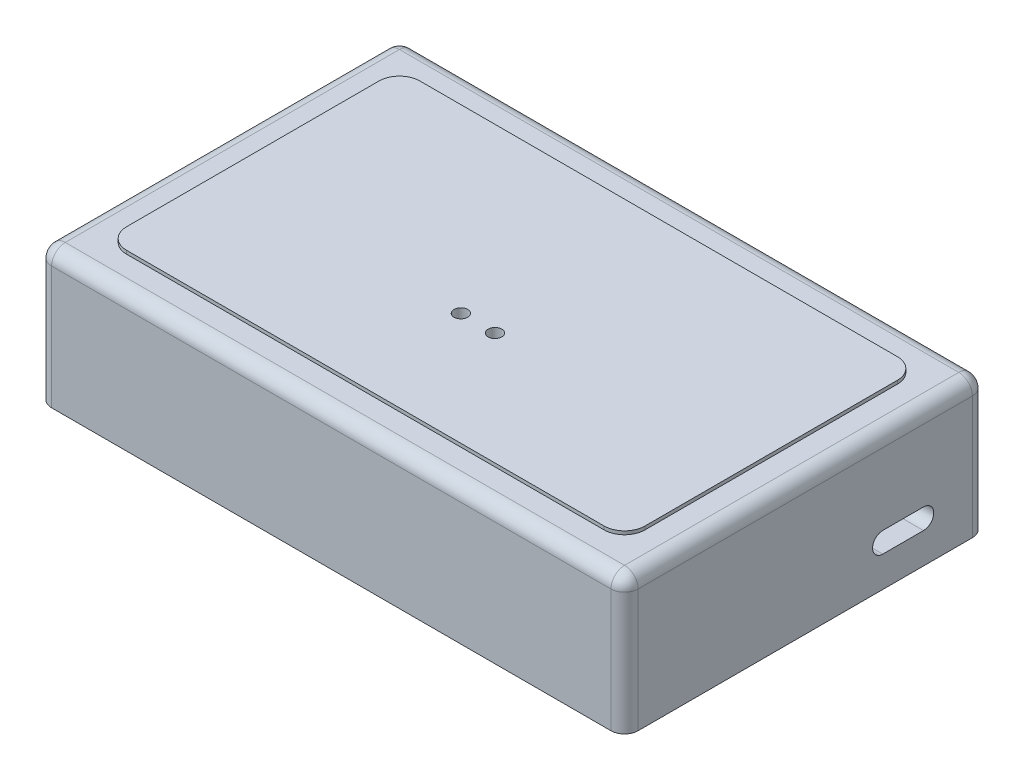
SolidWorks part; units mm, degrees
ref_plane "Front Plane" through (0, 0, 0) normal (0, 0, 1) x (1, 0, 0)
ref_plane "Top Plane" through (0, 0, 0) normal (0, 1, 0) x (1, 0, 0)
ref_plane "Right Plane" through (0, 0, 0) normal (1, 0, 0) x (0, 0, -1)
sketch "Sketch1" plane through (0, 0, 0) normal (0, 1, 0) x (1, 0, 0)
  line L0 (-73.2781, 0) -> (70.2249, 0) construction
  line L1 (0, -52.0325) -> (0, 55.0858) construction
  line L3 (-41, 26.5) -> (41, 26.5)
  line L4 (-43, 24.5) -> (-43, -24.5)
  line L5 (-41, -26.5) -> (41, -26.5)
  line L6 (43, 24.5) -> (43, -24.5)
  line L7 (-43, 26.5) -> (43, -26.5) construction
  line L8 (-43, -26.5) -> (43, 26.5) construction
  arc A0 (41, 26.5) -> (43, 24.5) centre (41, 24.5) cw
  arc A1 (41, -26.5) -> (43, -24.5) centre (41, -24.5) ccw
  arc A2 (-43, -24.5) -> (-41, -26.5) centre (-41, -24.5) ccw
  arc A3 (-41, 26.5) -> (-43, 24.5) centre (-41, 24.5) ccw
  point P5 (0, 0)
  dimension "D3" = 2
  dimension "D1" = 86
  dimension "D2" = 53
extrude "Boss-Extrude1" add sketch "Sketch1" along normal blind 20
fillet "Fillet1" radius 2 8 edges at (-42.4142, 20, 25.9142) (-43, 20, 0) (-42.4142, 20, -25.9142) (0, 20, -26.5) (42.4142, 20, -25.9142) (42.4142, 20, 25.9142) (0, 20, 26.5) (43, 20, 0)
sketch "Sketch2" plane through (0, 20, 0) normal (0, 1, 0) x (1, 0, 0)
  line L1 (-35, 21.5) -> (35, 21.5)
  line L2 (-38, 18.5) -> (-38, -18.5)
  line L3 (-35, -21.5) -> (35, -21.5)
  line L4 (38, 18.5) -> (38, -18.5)
  line L5 (-38, 21.5) -> (38, -21.5) construction
  line L6 (-38, -21.5) -> (38, 21.5) construction
  arc A0 (35, 21.5) -> (38, 18.5) centre (35, 18.5) cw
  arc A1 (35, -21.5) -> (38, -18.5) centre (35, -18.5) ccw
  arc A2 (-38, -18.5) -> (-35, -21.5) centre (-35, -18.5) ccw
  arc A3 (-35, 21.5) -> (-38, 18.5) centre (-35, 18.5) ccw
  point P0 (0, 0)
  dimension "D3" = 3
  dimension "D1" = 76
  dimension "D2" = 43
extrude "Boss-Extrude2" add sketch "Sketch2" along normal blind 0.5
sketch "Sketch3" plane through (0, 0, 0) normal (0, -1, 0) x (1, 0, 0)
  line L1 (-37, 23.5) -> (37, 23.5)
  line L2 (-40, 20.5) -> (-40, -20.5)
  line L3 (-37, -23.5) -> (37, -23.5)
  line L4 (40, 20.5) -> (40, -20.5)
  line L5 (-40, 23.5) -> (40, -23.5) construction
  line L6 (-40, -23.5) -> (40, 23.5) construction
  arc A0 (37, 23.5) -> (40, 20.5) centre (37, 20.5) cw
  arc A1 (37, -23.5) -> (40, -20.5) centre (37, -20.5) ccw
  arc A2 (-40, -20.5) -> (-37, -23.5) centre (-37, -20.5) ccw
  arc A3 (-37, 23.5) -> (-40, 20.5) centre (-37, 20.5) ccw
  point P0 (0, 0)
  dimension "D3" = 3
  dimension "D1" = 47
  dimension "D2" = 80
extrude "Cut-Extrude1" cut sketch "Sketch3" against normal blind 17
sketch "Sketch4" plane through (0, 0, 0) normal (0, -1, 0) x (1, 0, 0)
  line L1 (38.25, -24.75) -> (-38.25, -24.75)
  line L2 (41.25, -21.75) -> (41.25, 21.75)
  line L3 (38.25, 24.75) -> (-38.25, 24.75)
  line L4 (-41.25, -21.75) -> (-41.25, 21.75)
  line L5 (41.25, -24.75) -> (-41.25, 24.75) construction
  line L6 (41.25, 24.75) -> (-41.25, -24.75) construction
  arc A0 (41.25, 21.75) -> (38.25, 24.75) centre (38.25, 21.75) ccw
  arc A1 (38.25, -24.75) -> (41.25, -21.75) centre (38.25, -21.75) ccw
  arc A2 (-38.25, -24.75) -> (-41.25, -21.75) centre (-38.25, -21.75) cw
  arc A3 (-38.25, 24.75) -> (-41.25, 21.75) centre (-38.25, 21.75) ccw
  point P0 (0, 0)
  dimension "D3" = 3
  dimension "D1" = 82.5
  dimension "D2" = 49.5
extrude "Cut-Extrude2" cut sketch "Sketch4" against normal blind 3
sketch "Sketch5" plane through (0, 20.5, 0) normal (0, 1, 0) x (1, 0, 0)
  line L0 (-49.7547, 0) -> (54.7002, 0) construction
  line L1 (0, -36.1272) -> (0, 40.4453) construction
  line L2 (-49.7547, 6) -> (54.7002, 6) construction
  line L3 (-49.7547, -6) -> (54.7002, -6) construction
  line L4 (6, -36.1272) -> (6, 40.4453) construction
  line L5 (-6, -36.1272) -> (-6, 40.4453) construction
  line L6 (-35.3104, -5) -> (31.3979, -5) construction
  circle A0 centre (-2.5, -5) radius 1
  circle A1 centre (2.5, -5) radius 1
  dimension "D4" = 2.5
  dimension "D1" = 6
  dimension "D2" = 6
  dimension "D3" = 1
extrude "Cut-Extrude3" cut sketch "Sketch5" against normal blind 10
sketch "Sketch6" plane through (43, 0, 0) normal (1, 0, 0) x (0, 0, -1)
  line L0 (-34.1148, 6) -> (36.1019, 6) construction
  line L1 (14.3491, 7.9982) -> (14.3491, 1.3979) construction
  line L2 (11.3654, 7.5) -> (17.3328, 7.5)
  line L3 (11.3654, 4.5) -> (17.3328, 4.5)
  line L4 (-24.5, 0) -> (24.5, 0) construction
  circle A0 centre (17.3328, 6) radius 1.5
  circle A1 centre (11.3654, 6) radius 1.5
  dimension "D1" = 6
  dimension "D2" = 3
extrude "Cut-Extrude4" cut sketch "Sketch6" against normal blind 10 contours A1 | L2 A1 L3 A0 | A0 A1
